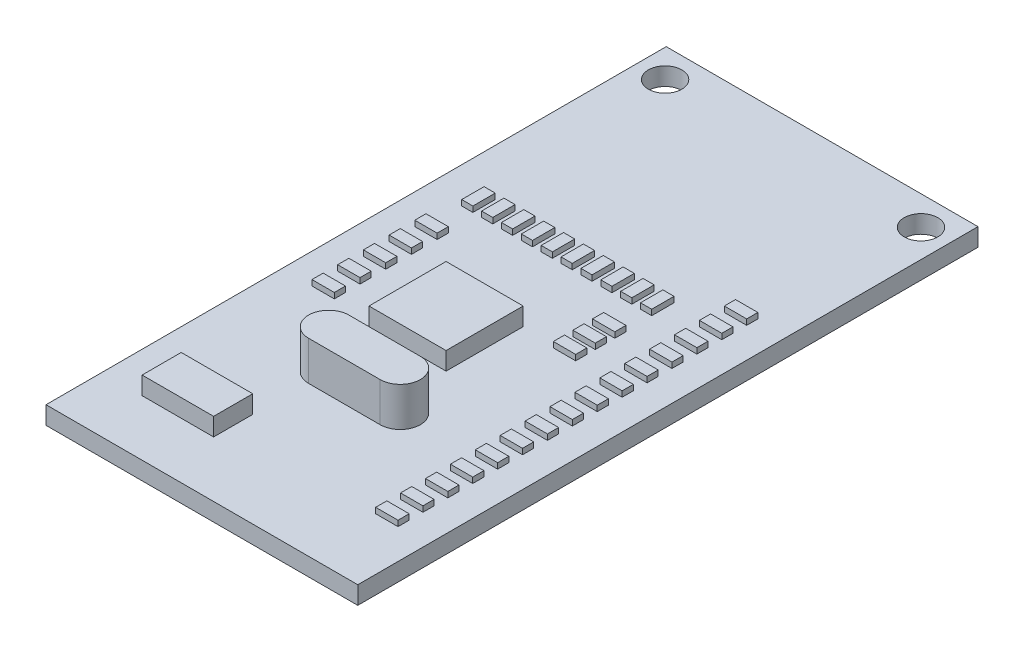
SolidWorks part; units mm, degrees
ref_plane "Спереди" through (0, 0, 0) normal (0, 0, 1) x (1, 0, 0)
ref_plane "Сверху" through (0, 0, 0) normal (0, 1, 0) x (1, 0, 0)
ref_plane "Справа" through (0, 0, 0) normal (1, 0, 0) x (0, 0, -1)
sketch "Эскиз1" plane through (0, 0, 0) normal (0, 1, 0) x (1, 0, 0)
  line L0 (-11.45, 25.15) -> (11.45, 25.15) construction
  line L1 (-13.95, 27.75) -> (13.95, 27.75)
  line L2 (-13.95, 27.75) -> (-13.95, -27.75)
  line L3 (-13.95, -27.75) -> (13.95, -27.75)
  line L4 (13.95, 27.75) -> (13.95, -27.75)
  line L5 (-13.95, 27.75) -> (13.95, -27.75) construction
  line L6 (-13.95, -27.75) -> (13.95, 27.75) construction
  circle A0 centre (-11.45, 25.15) radius 1.5
  circle A1 centre (11.45, 25.15) radius 1.5
  point P0 (0, 0)
  dimension "D3" = 3
  dimension "D5" = 1
  dimension "D1" = 27.9
  dimension "D2" = 55.5
  dimension "D4" = 1.1
  dimension "D6" = 1
extrude "Бобышка-Вытянуть1" add sketch "Эскиз1" along normal blind 1.6
sketch "Эскиз2" plane through (0, 1.6, 0) normal (0, 1, 0) x (1, 0, 0)
  line L0 (-13.95, -27.75) -> (13.95, -27.75) construction
  line L1 (1.35, -0.35) -> (-5.55, -0.35)
  line L2 (1.35, -0.35) -> (1.35, -7.25)
  line L3 (1.35, -7.25) -> (-5.55, -7.25)
  line L4 (-5.55, -0.35) -> (-5.55, -7.25)
  line L5 (-13.95, 27.75) -> (-13.95, -27.75) construction
  line L7 (-3.95, -19.25) -> (-10.35, -19.25)
  line L8 (-3.95, -19.25) -> (-3.95, -22.75)
  line L9 (-3.95, -22.75) -> (-10.35, -22.75)
  line L10 (-10.35, -19.25) -> (-10.35, -22.75)
  dimension "D1" = 6.9
  dimension "D2" = 27.4
  dimension "D3" = 15.3
  dimension "D4" = 6.4
  dimension "D5" = 3.5
  dimension "D6" = 3.6
  dimension "D7" = 5
extrude "Бобышка-Вытянуть2" add sketch "Эскиз2" along normal blind 1.6
sketch "Эскиз3" plane through (0, 1.6, 0) normal (0, 1, 0) x (1, 0, 0)
  line L0 (2.55, -12.55) -> (-3.85, -12.55) construction
  line L1 (2.55, -14.35) -> (-3.85, -14.35)
  line L2 (2.55, -10.75) -> (-3.85, -10.75)
  line L3 (13.95, -27.75) -> (13.95, 27.75) construction
  line L4 (-13.95, -27.75) -> (13.95, -27.75) construction
  arc A0 (2.55, -14.35) -> (2.55, -10.75) centre (2.55, -12.55) ccw
  arc A1 (-3.85, -10.75) -> (-3.85, -14.35) centre (-3.85, -12.55) ccw
  point P2 (-0.65, -12.55)
  dimension "D1" = 1.8
  dimension "D2" = 10
  dimension "D3" = 9.6
  dimension "D4" = 13.4
extrude "Бобышка-Вытянуть3" add sketch "Эскиз3" along normal blind 3.5
sketch "Эскиз4" plane through (0, 1.6, 0) normal (0, 1, 0) x (1, 0, 0)
  line L0 (-13.95, -27.75) -> (13.95, -27.75) construction
  line L1 (11.25, -20.45) -> (9.25, -20.45)
  line L2 (11.25, -20.45) -> (11.25, -21.45)
  line L3 (11.25, -21.45) -> (9.25, -21.45)
  line L4 (9.25, -20.45) -> (9.25, -21.45)
  line L5 (13.95, -27.75) -> (13.95, 27.75) construction
  line L6 (11.25, -18.2214) -> (9.25, -18.2214)
  line L7 (11.25, -18.2214) -> (11.25, -19.2214)
  line L8 (11.25, -19.2214) -> (9.25, -19.2214)
  line L9 (9.25, -18.2214) -> (9.25, -19.2214)
  line L10 (11.25, -15.9929) -> (9.25, -15.9929)
  line L11 (11.25, -15.9929) -> (11.25, -16.9929)
  line L12 (11.25, -16.9929) -> (9.25, -16.9929)
  line L13 (9.25, -15.9929) -> (9.25, -16.9929)
  line L14 (11.25, -13.7643) -> (9.25, -13.7643)
  line L15 (11.25, -13.7643) -> (11.25, -14.7643)
  line L16 (11.25, -14.7643) -> (9.25, -14.7643)
  line L17 (9.25, -13.7643) -> (9.25, -14.7643)
  line L18 (11.25, -11.5357) -> (9.25, -11.5357)
  line L19 (11.25, -11.5357) -> (11.25, -12.5357)
  line L20 (11.25, -12.5357) -> (9.25, -12.5357)
  line L21 (9.25, -11.5357) -> (9.25, -12.5357)
  line L22 (11.25, -9.3071) -> (9.25, -9.3071)
  line L23 (11.25, -9.3071) -> (11.25, -10.3071)
  line L24 (11.25, -10.3071) -> (9.25, -10.3071)
  line L25 (9.25, -9.3071) -> (9.25, -10.3071)
  line L26 (11.25, -7.0786) -> (9.25, -7.0786)
  line L27 (11.25, -7.0786) -> (11.25, -8.0786)
  line L28 (11.25, -8.0786) -> (9.25, -8.0786)
  line L29 (9.25, -7.0786) -> (9.25, -8.0786)
  line L30 (11.25, -4.85) -> (9.25, -4.85)
  line L31 (11.25, -4.85) -> (11.25, -5.85)
  line L32 (11.25, -5.85) -> (9.25, -5.85)
  line L33 (9.25, -4.85) -> (9.25, -5.85)
  line L34 (11.25, -2.6214) -> (9.25, -2.6214)
  line L35 (11.25, -2.6214) -> (11.25, -3.6214)
  line L36 (11.25, -3.6214) -> (9.25, -3.6214)
  line L37 (9.25, -2.6214) -> (9.25, -3.6214)
  line L38 (11.25, -0.3929) -> (9.25, -0.3929)
  line L39 (11.25, -0.3929) -> (11.25, -1.3929)
  line L40 (11.25, -1.3929) -> (9.25, -1.3929)
  line L41 (9.25, -0.3929) -> (9.25, -1.3929)
  line L42 (11.25, 1.8357) -> (9.25, 1.8357)
  line L43 (11.25, 1.8357) -> (11.25, 0.8357)
  line L44 (11.25, 0.8357) -> (9.25, 0.8357)
  line L45 (9.25, 1.8357) -> (9.25, 0.8357)
  line L46 (11.25, 4.0643) -> (9.25, 4.0643)
  line L47 (11.25, 4.0643) -> (11.25, 3.0643)
  line L48 (11.25, 3.0643) -> (9.25, 3.0643)
  line L49 (9.25, 4.0643) -> (9.25, 3.0643)
  line L50 (11.25, 6.2929) -> (9.25, 6.2929)
  line L51 (11.25, 6.2929) -> (11.25, 5.2929)
  line L52 (11.25, 5.2929) -> (9.25, 5.2929)
  line L53 (9.25, 6.2929) -> (9.25, 5.2929)
  line L54 (11.25, 8.5214) -> (9.25, 8.5214)
  line L55 (11.25, 8.5214) -> (11.25, 7.5214)
  line L56 (11.25, 7.5214) -> (9.25, 7.5214)
  line L57 (9.25, 8.5214) -> (9.25, 7.5214)
  line L58 (11.25, 10.75) -> (9.25, 10.75)
  line L59 (11.25, 10.75) -> (11.25, 9.75)
  line L60 (11.25, 9.75) -> (9.25, 9.75)
  line L61 (9.25, 10.75) -> (9.25, 9.75)
  line L62 (-13.95, 27.75) -> (-13.95, -27.75) construction
  line L63 (-10.75, 8.25) -> (-9.75, 8.25)
  line L64 (-10.75, 8.25) -> (-10.75, 6.25)
  line L65 (-10.75, 6.25) -> (-9.75, 6.25)
  line L66 (-9.75, 8.25) -> (-9.75, 6.25)
  line L67 (-7.9722, 8.25) -> (-7.9722, 6.25)
  line L68 (-8.9722, 6.25) -> (-7.9722, 6.25)
  line L69 (-8.9722, 8.25) -> (-8.9722, 6.25)
  line L70 (-8.9722, 8.25) -> (-7.9722, 8.25)
  line L71 (-6.1944, 8.25) -> (-6.1944, 6.25)
  line L72 (-7.1944, 6.25) -> (-6.1944, 6.25)
  line L73 (-7.1944, 8.25) -> (-7.1944, 6.25)
  line L74 (-7.1944, 8.25) -> (-6.1944, 8.25)
  line L75 (-4.4167, 8.25) -> (-4.4167, 6.25)
  line L76 (-5.4167, 6.25) -> (-4.4167, 6.25)
  line L77 (-5.4167, 8.25) -> (-5.4167, 6.25)
  line L78 (-5.4167, 8.25) -> (-4.4167, 8.25)
  line L79 (-2.6389, 8.25) -> (-2.6389, 6.25)
  line L80 (-3.6389, 6.25) -> (-2.6389, 6.25)
  line L81 (-3.6389, 8.25) -> (-3.6389, 6.25)
  line L82 (-3.6389, 8.25) -> (-2.6389, 8.25)
  line L83 (-0.8611, 8.25) -> (-0.8611, 6.25)
  line L84 (-1.8611, 6.25) -> (-0.8611, 6.25)
  line L85 (-1.8611, 8.25) -> (-1.8611, 6.25)
  line L86 (-1.8611, 8.25) -> (-0.8611, 8.25)
  line L87 (0.9167, 8.25) -> (0.9167, 6.25)
  line L88 (-0.0833, 6.25) -> (0.9167, 6.25)
  line L89 (-0.0833, 8.25) -> (-0.0833, 6.25)
  line L90 (-0.0833, 8.25) -> (0.9167, 8.25)
  line L91 (2.6944, 8.25) -> (2.6944, 6.25)
  line L92 (1.6944, 6.25) -> (2.6944, 6.25)
  line L93 (1.6944, 8.25) -> (1.6944, 6.25)
  line L94 (1.6944, 8.25) -> (2.6944, 8.25)
  line L95 (4.4722, 8.25) -> (4.4722, 6.25)
  line L96 (3.4722, 6.25) -> (4.4722, 6.25)
  line L97 (3.4722, 8.25) -> (3.4722, 6.25)
  line L98 (3.4722, 8.25) -> (4.4722, 8.25)
  line L99 (6.25, 8.25) -> (6.25, 6.25)
  line L100 (5.25, 6.25) -> (6.25, 6.25)
  line L101 (5.25, 8.25) -> (5.25, 6.25)
  line L102 (5.25, 8.25) -> (6.25, 8.25)
  line L103 (13.95, -27.75) -> (13.95, 27.75) construction
  line L104 (6.35, 3.85) -> (4.35, 3.85)
  line L105 (6.35, 3.85) -> (6.35, 2.85)
  line L106 (6.35, 2.85) -> (4.35, 2.85)
  line L107 (4.35, 3.85) -> (4.35, 2.85)
  line L108 (6.35, 2.1) -> (6.35, 1.1)
  line L109 (6.35, 1.1) -> (4.35, 1.1)
  line L110 (4.35, 2.1) -> (4.35, 1.1)
  line L111 (6.35, 2.1) -> (4.35, 2.1)
  line L112 (6.35, 0.35) -> (6.35, -0.65)
  line L113 (6.35, -0.65) -> (4.35, -0.65)
  line L114 (4.35, 0.35) -> (4.35, -0.65)
  line L115 (6.35, 0.35) -> (4.35, 0.35)
  line L116 (-9.25, 1.25) -> (-9.25, 0.25)
  line L117 (-11.25, 3.55) -> (-9.25, 3.55)
  line L118 (-11.25, 3.55) -> (-11.25, 2.55)
  line L119 (-11.25, 2.55) -> (-9.25, 2.55)
  line L120 (-9.25, 3.55) -> (-9.25, 2.55)
  line L121 (-11.25, 1.25) -> (-9.25, 1.25)
  line L122 (-11.25, 1.25) -> (-11.25, 0.25)
  line L123 (-11.25, 0.25) -> (-9.25, 0.25)
  line L124 (-9.25, -1.05) -> (-9.25, -2.05)
  line L125 (-11.25, -1.05) -> (-9.25, -1.05)
  line L126 (-11.25, -1.05) -> (-11.25, -2.05)
  line L127 (-11.25, -2.05) -> (-9.25, -2.05)
  line L128 (-9.25, -3.35) -> (-9.25, -4.35)
  line L129 (-11.25, -3.35) -> (-9.25, -3.35)
  line L130 (-11.25, -3.35) -> (-11.25, -4.35)
  line L131 (-11.25, -4.35) -> (-9.25, -4.35)
  line L132 (-9.25, -5.65) -> (-9.25, -6.65)
  line L133 (-11.25, -5.65) -> (-9.25, -5.65)
  line L134 (-11.25, -5.65) -> (-11.25, -6.65)
  line L135 (-11.25, -6.65) -> (-9.25, -6.65)
  point P112 (5.35, -0.65)
  dimension "D1" = 1
  dimension "D2" = 2
  dimension "D3" = 6.3
  dimension "D4" = 2.7
  dimension "D6" = 38.5
  dimension "D7" = 3.2
  dimension "D8" = 36
  dimension "D10" = 17
  dimension "D11" = 9.6
  dimension "D12" = 31.6
  dimension "D14" = 4.5
  dimension "D15" = 2.7
  dimension "D16" = 31.3
  dimension "D18" = 10.2
  dimension "D5" = 15
  dimension "D9" = 10
  dimension "D13" = 3
  dimension "D17" = 5
extrude "Бобышка-Вытянуть4" add sketch "Эскиз4" along normal blind 0.5
